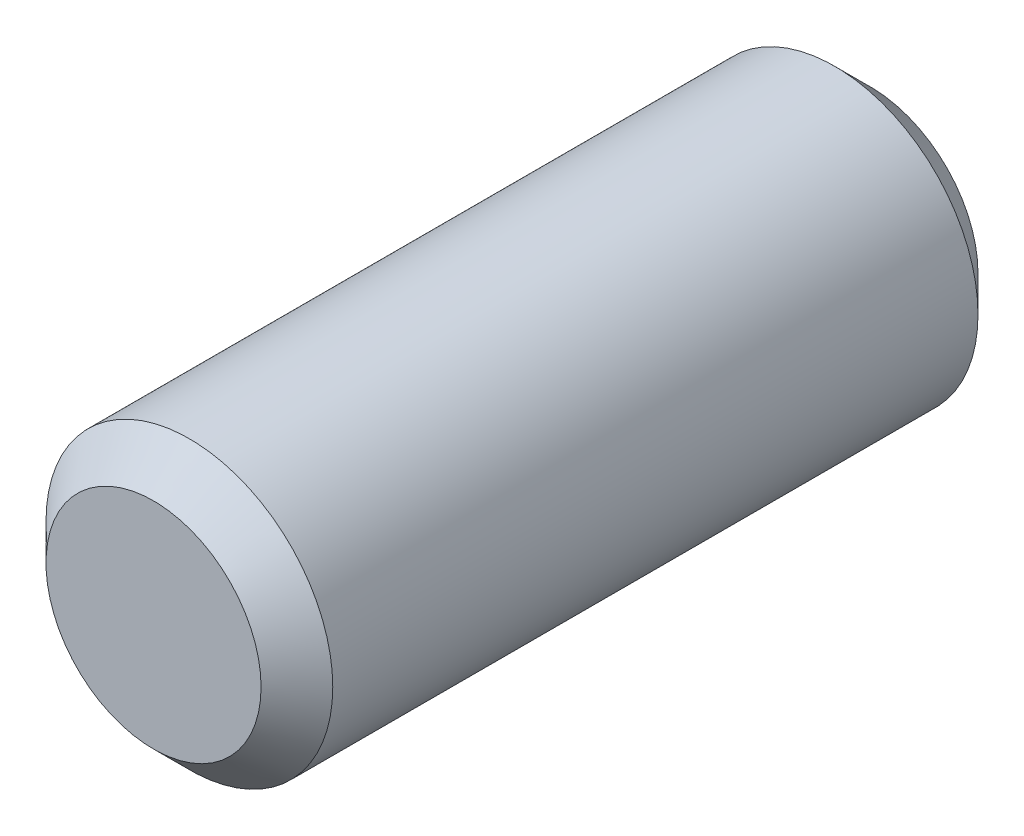
SolidWorks part; units mm, degrees
material "40Х ГОСТ 4543-71"
ref_plane "Спереди" through (0, 0, 0) normal (0, 0, 1) x (1, 0, 0)
ref_plane "Сверху" through (0, 0, 0) normal (0, 1, 0) x (1, 0, 0)
ref_plane "Справа" through (0, 0, 0) normal (1, 0, 0) x (0, 0, -1)
sketch "Sketch1" plane through (0, 0, 0) normal (0, 0, 1) x (1, 0, 0)
  line L0 (0, 48.6842) -> (0, -51.3158) construction
  line L1 (-51.8421, 0) -> (48.1579, 0) construction
  circle A0 centre (0, 0) radius 4
  dimension "D1" = 8
extrude "Boss-Extrude1" add sketch "Sketch1" along normal mid plane 20
chamfer "Chamfer1" distance 1 angle 45 2 edges at (4, 0, -10) (4, 0, 10)
